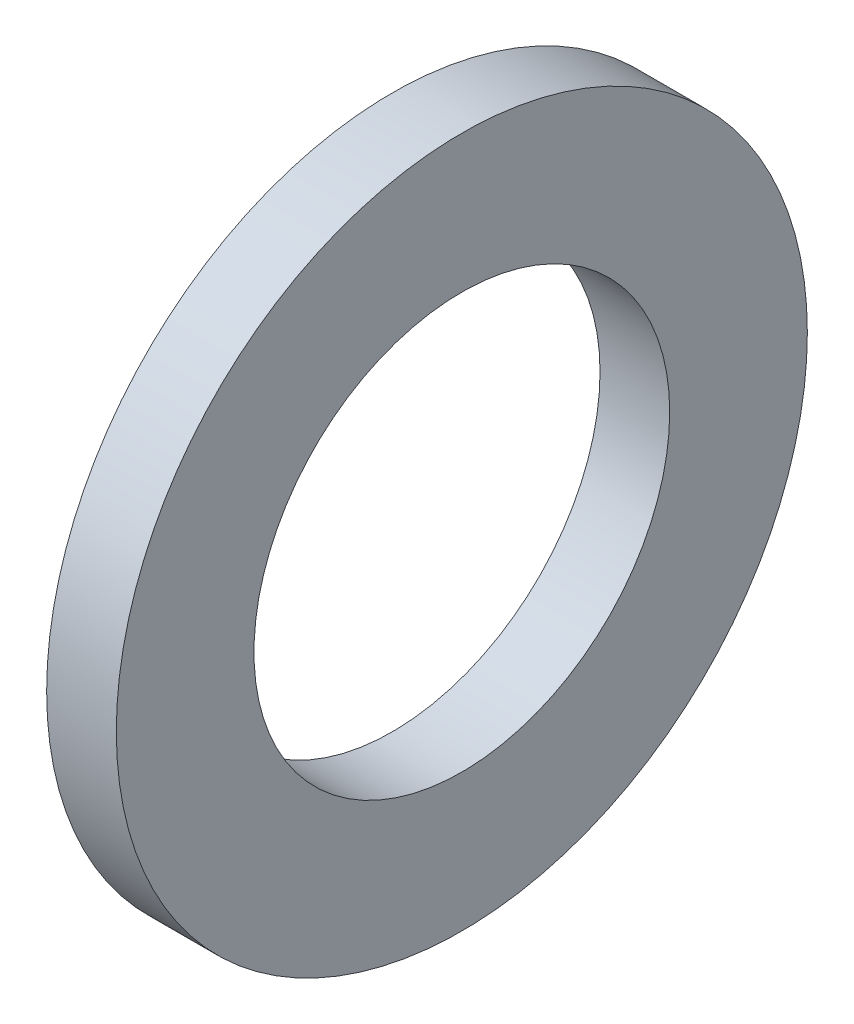
SolidWorks part; units mm, degrees
ref_plane "Front Plane" through (0, 0, 0) normal (0, 0, 1) x (1, 0, 0)
ref_plane "Top Plane" through (0, 0, 0) normal (0, 1, 0) x (1, 0, 0)
ref_plane "Right Plane" through (0, 0, 0) normal (1, 0, 0) x (0, 0, -1)
sketch "Sketch1" plane through (0, 0, 0) normal (1, 0, 0) x (0, 0, -1)
  circle A0 centre (0, 0) radius 15.875
  circle A1 centre (0, 0) radius 9.5504
  dimension "OD" = 31.75
  dimension "Shaft Dia" = 19.1008
extrude "Extrude1" add sketch "Sketch1" along normal blind 3.2004
